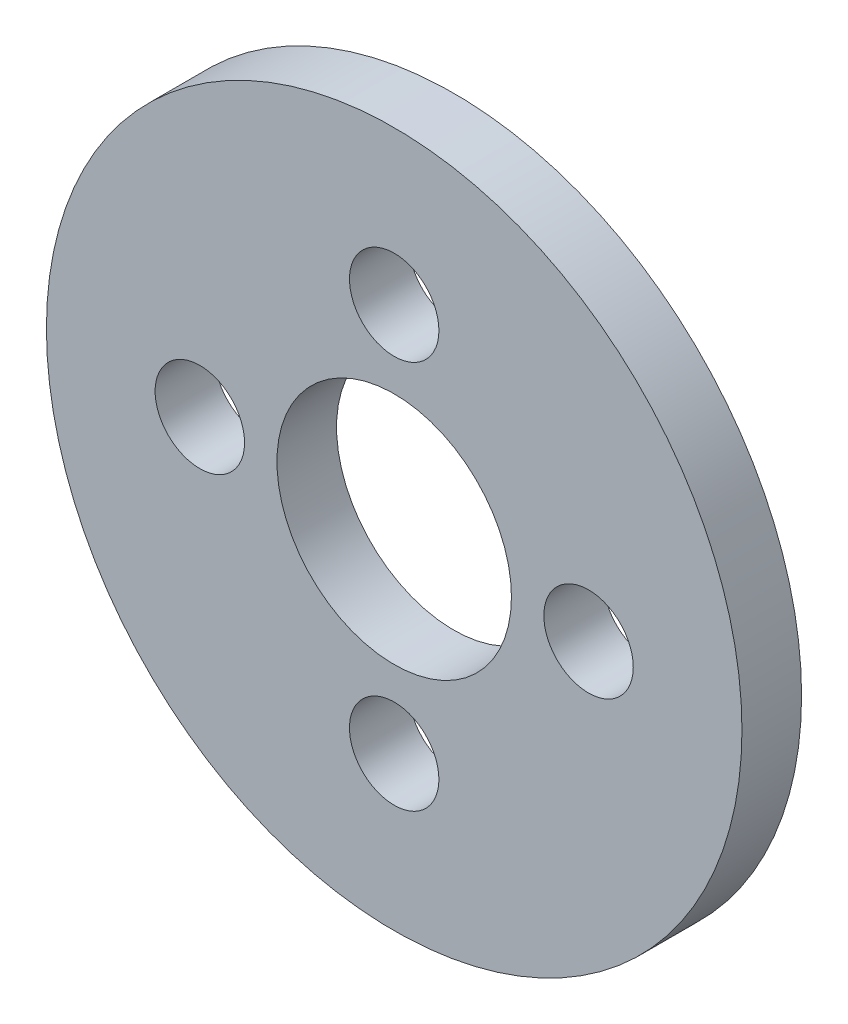
SolidWorks part; units mm, degrees
ref_plane "Front Plane" through (0, 0, 0) normal (0, 0, 1) x (1, 0, 0)
ref_plane "Top Plane" through (0, 0, 0) normal (0, 1, 0) x (1, 0, 0)
ref_plane "Right Plane" through (0, 0, 0) normal (1, 0, 0) x (0, 0, -1)
sketch "Sketch1" plane through (0, 0, 0) normal (0, 0, 1) x (1, 0, 0)
  circle A0 centre (0, 0) radius 5.9
  circle A1 centre (0, 0) radius 17.5
  dimension "D1" = 11.8
  dimension "D2" = 35
extrude "Boss-Extrude1" add sketch "Sketch1" along normal blind 3 contours A1 A0
sketch "Sketch3" plane through (0, 0, 3) normal (0, 0, 1) x (1, 0, 0)
  circle A0 centre (0, 0) radius 9.78
  circle A1 centre (0, 9.78) radius 2.25
  circle A2 centre (9.78, 0) radius 2.25
  circle A3 centre (0, -9.78) radius 2.25
  circle A4 centre (-9.78, 0) radius 2.25
  point P12 (0, 0)
  dimension "D1" = 19.56
  dimension "D2" = 4.5
  dimension "D3" = 4
extrude "Cut-Extrude2" cut sketch "Sketch3" against normal blind 3 contours A0 A3 | A0 A3 | A0 A2 | A0 A2 | A0 A1 | A0 A1 | A0 A4 | A0 A4
